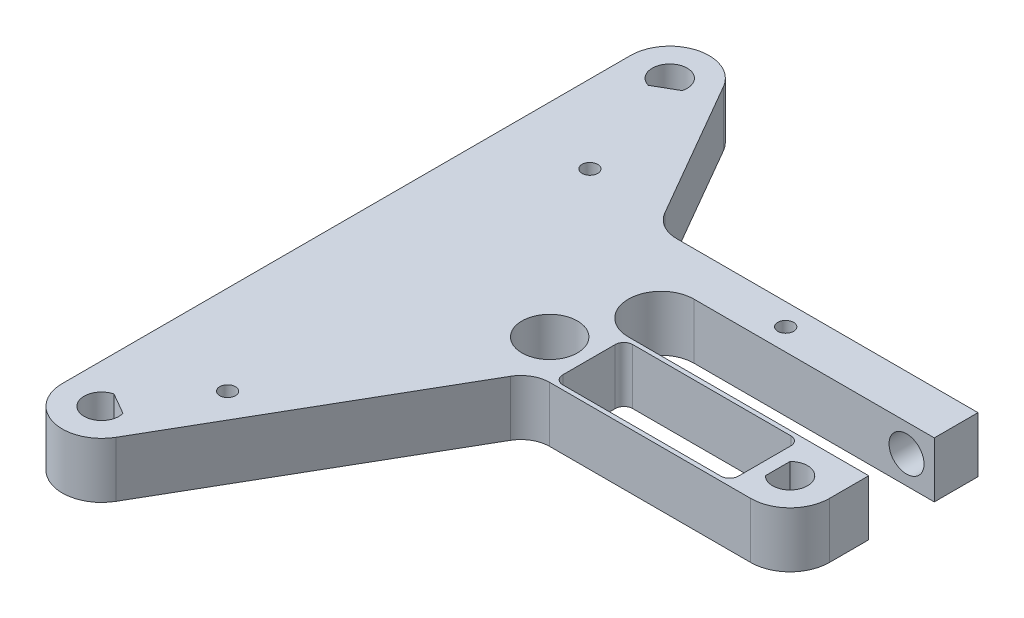
SolidWorks part; units mm, degrees
ref_plane "Front Plane" through (0, 0, 0) normal (0, 0, 1) x (1, 0, 0)
ref_plane "Top Plane" through (0, 0, 0) normal (0, 1, 0) x (1, 0, 0)
ref_plane "Right Plane" through (0, 0, 0) normal (1, 0, 0) x (0, 0, -1)
sketch "Sketch1" plane through (0, 0, 0) normal (0, 1, 0) x (1, 0, 0)
  line L0 (64, 0) -> (64, 9)
  line L1 (9, 24) -> (64, 24)
  line L2 (15, 0) -> (55, 0) construction
  line L3 (-42, 57) -> (72, 57) construction
  line L4 (-42, 57) -> (-42, -57) construction
  line L5 (-42, -57) -> (72, -57) construction
  line L6 (72, 57) -> (72, -57) construction
  line L7 (52.1716, 2.8284) -> (52.1716, -2.8284)
  line L8 (52.1716, 2.8284) -> (55, 0) construction
  line L9 (55, 0) -> (52.1716, -2.8284) construction
  line L13 (-38.563, 61.1363) -> (-33.6641, 63.9647)
  line L14 (-37.5278, 65) -> (0, 0) construction
  line L15 (-38.563, -61.1363) -> (-33.6641, -63.9647)
  line L16 (-46.5278, 65) -> (-46.5278, -65)
  line L21 (64, 9) -> (9, 9)
  line L22 (-29.7335, 69.5) -> (-11.4027, 37.75)
  line L23 (-29.7335, -69.5) -> (3.2942, -12.2942)
  line L24 (9, -9) -> (55, -9)
  line L25 (64, 24) -> (64, 34)
  line L26 (9, 8) -> (49.1716, 8)
  line L27 (9, 8) -> (9, -8)
  line L28 (9, -8) -> (49.1716, -8)
  line L29 (49.1716, 8) -> (49.1716, -8)
  line L30 (64, 34) -> (-4.9075, 34)
  line L31 (25, 29) -> (25, 24) construction
  line L32 (25, 29) -> (25, 34) construction
  circle A4 centre (15, 0) radius 57 construction
  arc A5 (52.1716, 2.8284) -> (52.1716, -2.8284) centre (55, 0) cw
  arc A6 (-33.6641, 63.9647) -> (-38.563, 61.1363) centre (-37.5278, 65) ccw
  arc A7 (-33.6641, -63.9647) -> (-38.563, -61.1363) centre (-37.5278, -65) cw
  arc A9 (-29.7335, 69.5) -> (-46.5278, 65) centre (-37.5278, 65) ccw
  arc A10 (-46.5278, -65) -> (-29.7335, -69.5) centre (-37.5278, -65) ccw
  circle A12 centre (0, 0) radius 6.35
  arc A15 (55, -9) -> (64, 0) centre (55, 0) ccw
  arc A16 (9, 9) -> (9, 24) centre (9, 16.5) cw
  arc A17 (-11.4027, 37.75) -> (-4.9075, 34) centre (-4.9075, 41.5) ccw
  circle A18 centre (25, 29) radius 1.8
  circle A19 centre (-28.7, 37.9) radius 1.8
  circle A20 centre (-26.1, -47.6) radius 1.8
  arc A21 (9, -9) -> (3.2942, -12.2942) centre (9, -15.5885) ccw
  point P2 (49.1716, 0)
  point P9 (15, 0)
  dimension "D4" = 9
  dimension "D6" = 25
  dimension "D7" = 53.7
  dimension "D8" = 114
  dimension "D9" = 4
  dimension "D11" = 120
  dimension "D14" = 12.7
  dimension "D15" = 9
  dimension "D16" = 8.9
  dimension "D17" = 1
  dimension "D2" = 15
  dimension "D5" = 3.6
  dimension "D3" = 10
  dimension "D10" = 55
  dimension "D12" = 15
  dimension "D13" = 65
  dimension "D18" = 1
  dimension "D19" = 3
  dimension "D20" = 51.1
  dimension "D21" = 76.6
extrude "Boss-Extrude1" add sketch "Sketch1" along normal blind 12.7
fillet "Fillet1" radius 2 4 edges at (9, 6.35, 8) (9, 6.35, -8) (49.1716, 6.35, 8) (49.1716, 6.35, -8)
sketch "Sketch2" plane through (0, 0, -34) normal (0, 0, -1) x (-1, 0, 0)
  line L0 (-57.65, 6.35) -> (-57.65, 0) construction
  line L1 (-64, 0) -> (4.9075, 0) construction
  line L2 (-57.65, 6.35) -> (-57.65, 12.7) construction
  line L3 (-64, 12.7) -> (4.9075, 12.7) construction
  line L4 (-57.65, 6.35) -> (-64, 6.35) construction
  line L5 (-64, 12.7) -> (-64, 0) construction
  circle A0 centre (-57.65, 6.35) radius 4
  dimension "D1" = 8
extrude "Cut-Extrude1" cut sketch "Sketch2" against normal up to next
